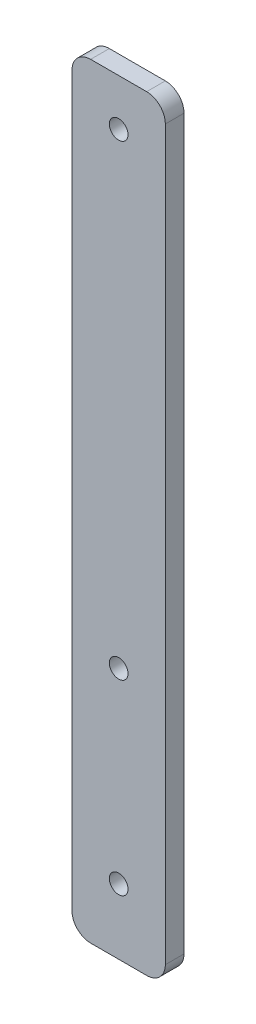
SolidWorks part; units mm, degrees
ref_plane "Front Plane" through (0, 0, 0) normal (0, 0, 1) x (1, 0, 0)
ref_plane "Top Plane" through (0, 0, 0) normal (0, 1, 0) x (1, 0, 0)
ref_plane "Right Plane" through (0, 0, 0) normal (1, 0, 0) x (0, 0, -1)
sketch "Sketch1" plane through (0, 0, 0) normal (0, 0, 1) x (1, 0, 0)
  line L1 (0, 0) -> (50, 0)
  line L2 (0, 0) -> (0, -410)
  line L3 (0, -410) -> (50, -410)
  line L4 (50, 0) -> (50, -410)
  circle A0 centre (25, -275) radius 5
  circle A1 centre (25, -25) radius 5
  point P9 (0, 0)
  dimension "D3" = 10
  dimension "D6" = 250
  dimension "D1" = 50
  dimension "D2" = 410
  dimension "D5" = 25
  dimension "D7" = 25
extrude "Boss-Extrude1" add sketch "Sketch1" along normal blind 10
fillet "Fillet1" radius 10 4 edges at (0, 0, 5) (50, 0, 5) (0, -410, 5) (50, -410, 5)
sketch "Sketch2" plane through (0, 0, 10) normal (0, 0, 1) x (1, 0, 0)
  line L0 (10, -410) -> (40, -410) construction
  line L1 (0, -10) -> (0, -400) construction
  circle A0 centre (25, -375) radius 5
  dimension "D1" = 10
  dimension "D2" = 35
  dimension "D3" = 25
extrude "Cut-Extrude1" cut sketch "Sketch2" against normal blind 10
